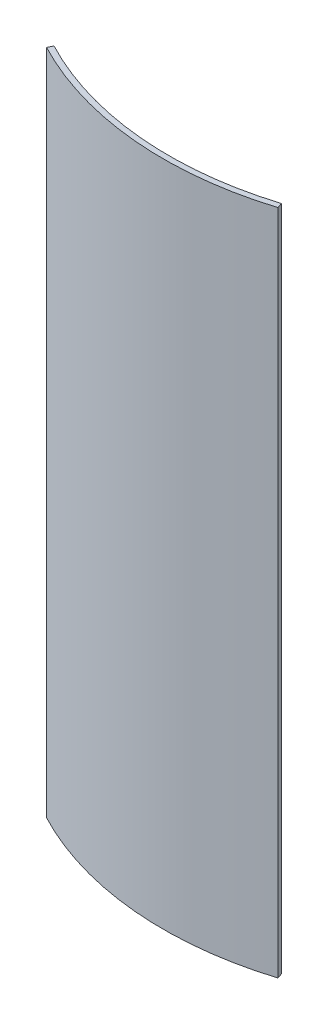
SolidWorks part; units mm, degrees
ref_plane "Front Plane" through (0, 0, 0) normal (0, 0, 1) x (1, 0, 0)
ref_plane "Top Plane" through (0, 0, 0) normal (0, 1, 0) x (1, 0, 0)
ref_plane "Right Plane" through (0, 0, 0) normal (1, 0, 0) x (0, 0, -1)
sketch "Sketch1" plane through (0, 0, 0) normal (0, 1, 0) x (1, 0, 0)
  line L0 (-34.8119, -66.3524) -> (-35.3862, -67.4852)
  line L1 (22.3025, -71.5339) -> (22.6974, -72.7411)
  circle A0 centre (0, 0) radius 76.2 construction
  arc A1 (-35.3862, -67.4852) -> (22.6974, -72.7411) centre (0, 0) ccw
  circle A2 centre (0, 0) radius 74.93 construction
  arc A3 (22.3025, -71.5339) -> (-34.8119, -66.3524) centre (0, 0) cw
extrude "Boss-Extrude1" add sketch "Sketch1" along normal blind 152.4
